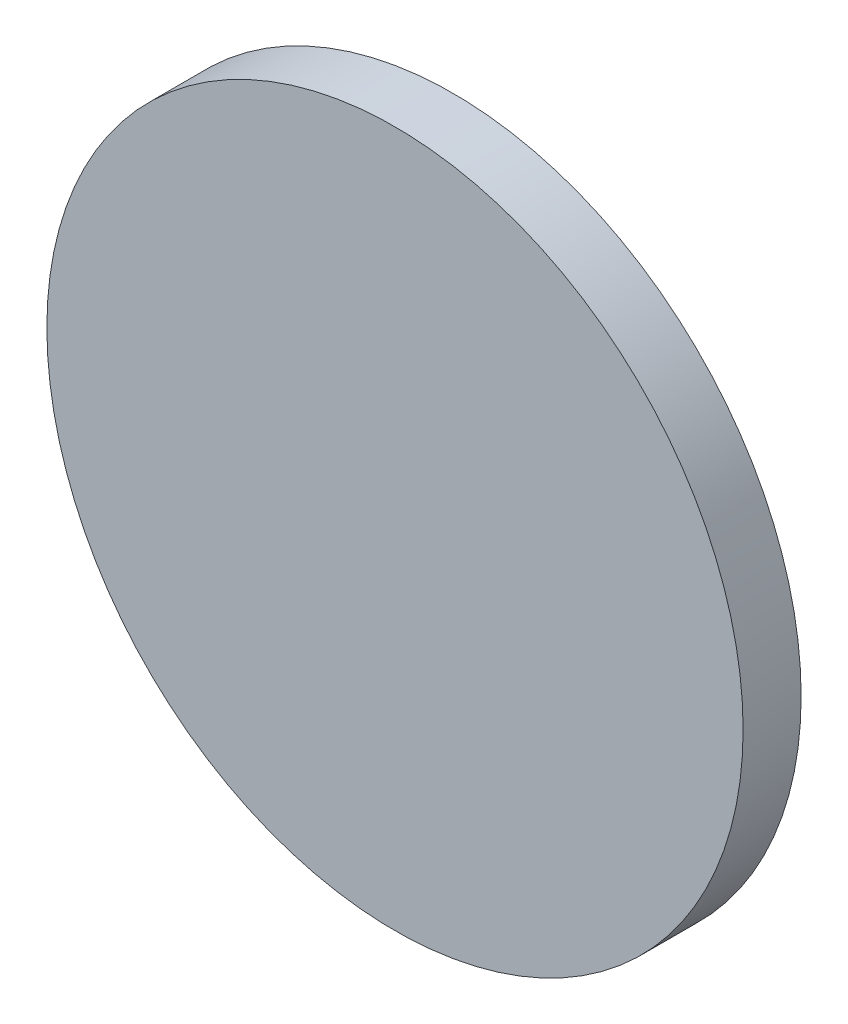
SolidWorks part; units mm, degrees
ref_plane "Front Plane" through (0, 0, 0) normal (0, 0, 1) x (1, 0, 0)
ref_plane "Top Plane" through (0, 0, 0) normal (0, 1, 0) x (1, 0, 0)
ref_plane "Right Plane" through (0, 0, 0) normal (1, 0, 0) x (0, 0, -1)
sketch "Sketch1" plane through (0, 0, 0) normal (0, 0, 1) x (1, 0, 0)
  circle A0 centre (0, 0) radius 38.1
extrude "Boss-Extrude1" add sketch "Sketch1" along normal blind 6.35
sketch "Sketch4" plane through (0, 0, 0) normal (0, 0, -1) x (-1, 0, 0)
  line L1 (-10.1, 30.02) -> (10.1, 30.02)
  line L2 (-10.1, 30.02) -> (-10.1, -10.02)
  line L3 (-10.1, -10.02) -> (10.1, -10.02)
  line L4 (10.1, 30.02) -> (10.1, -10.02)
  dimension "D1" = 10.02
  dimension "D2" = 30.02
  dimension "D3" = 10.1
  dimension "D4" = 10.1
extrude "Cut-Extrude1" cut sketch "Sketch4" against normal blind 5.3
